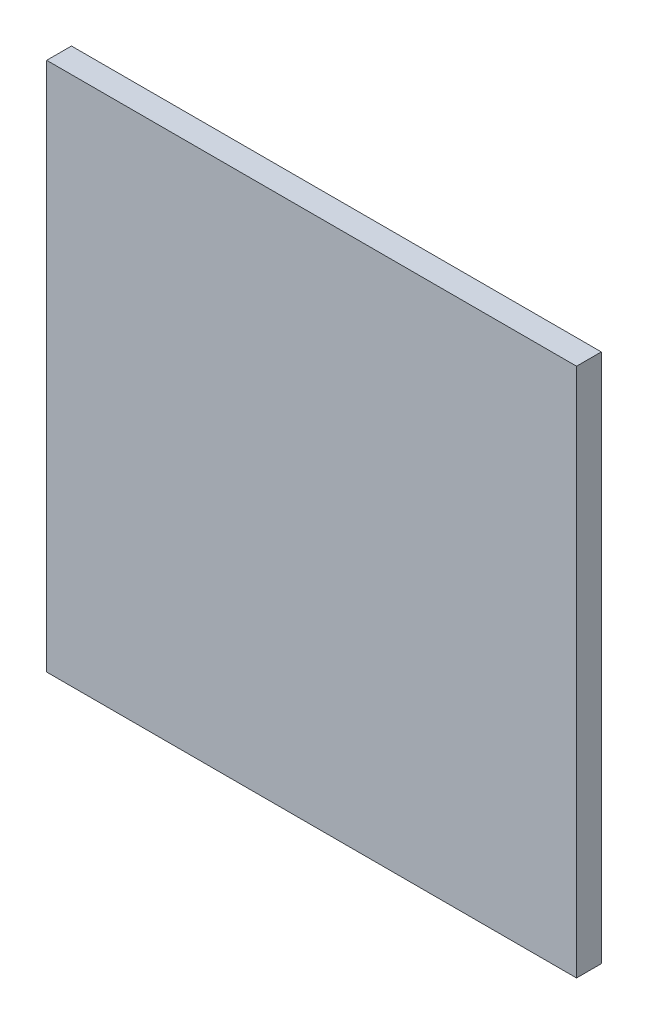
SolidWorks part; units mm, degrees
ref_plane "Front Plane" through (0, 0, 0) normal (0, 0, 1) x (1, 0, 0)
ref_plane "Top Plane" through (0, 0, 0) normal (0, 1, 0) x (1, 0, 0)
ref_plane "Right Plane" through (0, 0, 0) normal (1, 0, 0) x (0, 0, -1)
sketch "Sketch1" plane through (0, 0, 0) normal (0, 0, 1) x (1, 0, 0)
  line L1 (267.5, 267.5) -> (-267.5, 267.5)
  line L2 (267.5, 267.5) -> (267.5, -267.5)
  line L3 (267.5, -267.5) -> (-267.5, -267.5)
  line L4 (-267.5, 267.5) -> (-267.5, -267.5)
  line L5 (267.5, 267.5) -> (-267.5, -267.5) construction
  line L6 (267.5, -267.5) -> (-267.5, 267.5) construction
  point P0 (0, 0)
  dimension "D1" = 535
extrude "Boss-Extrude1" add sketch "Sketch1" along normal blind 25
